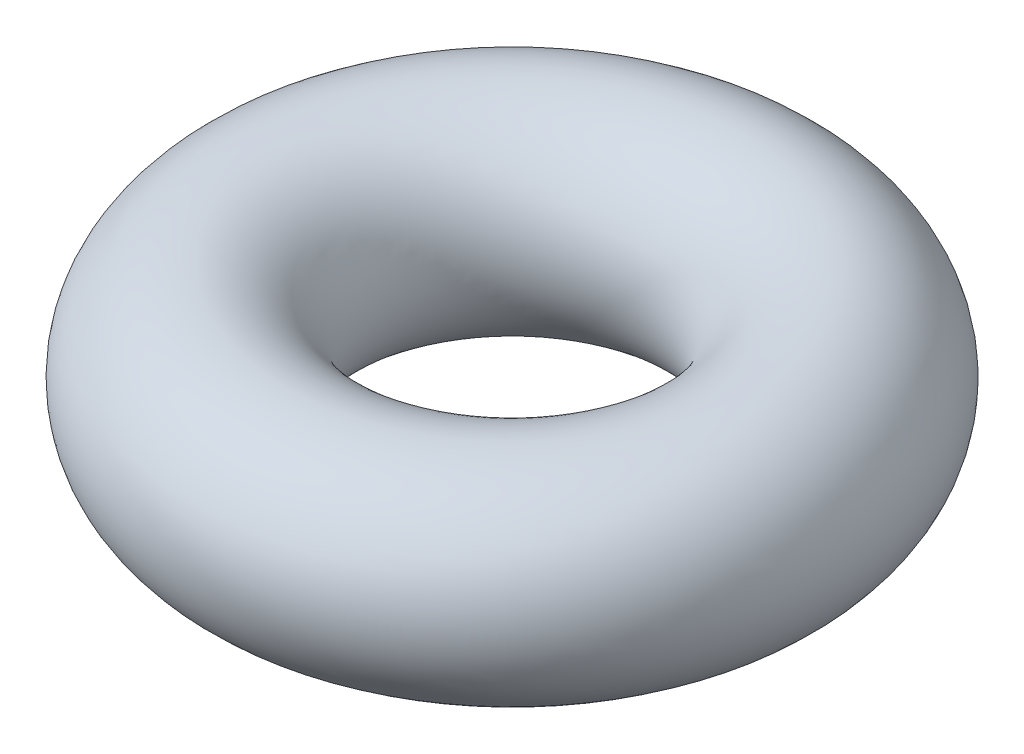
SolidWorks part; units mm, degrees
ref_plane "Front Plane" through (0, 0, 0) normal (0, 0, 1) x (1, 0, 0)
ref_plane "Top Plane" through (0, 0, 0) normal (0, 1, 0) x (1, 0, 0)
ref_plane "Right Plane" through (0, 0, 0) normal (1, 0, 0) x (0, 0, -1)
sketch "Sketch1" plane through (0, 0, 0) normal (0, 1, 0) x (1, 0, 0)
  circle A0 centre (0, 0) radius 2
  dimension "D1" = 4
sketch "Sketch2" plane through (0, 0, 0) normal (0, 0, 1) x (1, 0, 0)
  line L0 (2, 0) -> (-2, 0) construction
  circle A0 centre (-2, 0) radius 0.9
  point P4 (-1.8142, 0)
  point P5 (0, 0)
  point P6 (-2, 0)
  point P7 (-2, 0)
  point P8 (0, 0)
  point P9 (-2, 0)
  point P10 (-1.7282, 0)
  point P11 (0, 0)
  point P12 (0, 0)
  dimension "D1" = 1.8
sweep "Sweep1" add profiles "Sketch2" path "Sketch1"
